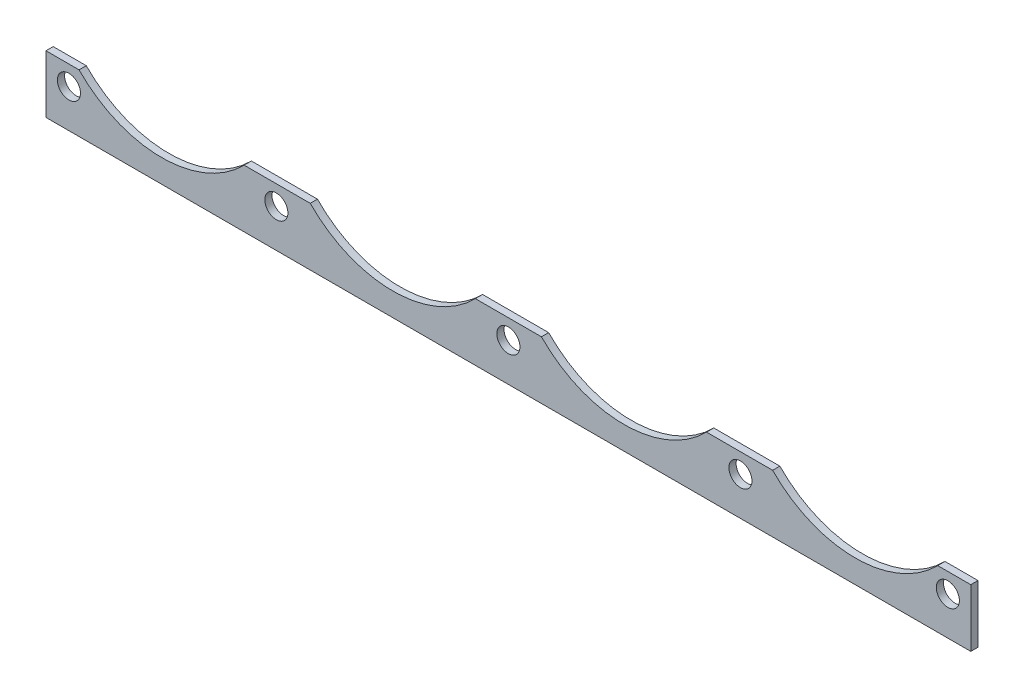
SolidWorks part; units mm, degrees
ref_plane "Front Plane" through (0, 0, 0) normal (0, 0, 1) x (1, 0, 0)
ref_plane "Top Plane" through (0, 0, 0) normal (0, 1, 0) x (1, 0, 0)
ref_plane "Right Plane" through (0, 0, 0) normal (1, 0, 0) x (0, 0, -1)
sketch "Sketch1" plane through (0, 0, 0) normal (0, 0, 1) x (1, 0, 0)
  line L0 (0, 12.7) -> (0, 0) construction
  line L1 (-101.6, 12.7) -> (101.6, 12.7)
  line L2 (-101.6, 12.7) -> (-101.6, 0)
  line L3 (-101.6, 0) -> (101.6, 0)
  line L4 (101.6, 12.7) -> (101.6, 0)
  circle A0 centre (-76.2, 30.48) radius 25.4
  circle A1 centre (-25.4, 30.48) radius 25.4
  circle A2 centre (25.4, 30.48) radius 25.4
  circle A3 centre (76.2, 30.48) radius 25.4
  circle A4 centre (-96.562, 8.3989) radius 2.54
  circle A5 centre (-50.9847, 8.3989) radius 2.54
  circle A6 centre (96.562, 8.3989) radius 2.54
  circle A7 centre (0, 8.3989) radius 2.54
  circle A8 centre (50.9847, 8.3989) radius 2.54
  dimension "D3" = 50.8
  dimension "D4" = 4
  dimension "D5" = 30.48
  dimension "D6" = 3
  dimension "D1" = 203.2
  dimension "D2" = 12.7
extrude "Boss-Extrude1" add sketch "Sketch1" along normal mid plane 1.5875 contours L0 L1 A1 A0 L2 L3 A7 A4 A5 | L1 L0 A7 L3 L4 A3 A2 A6 A8
